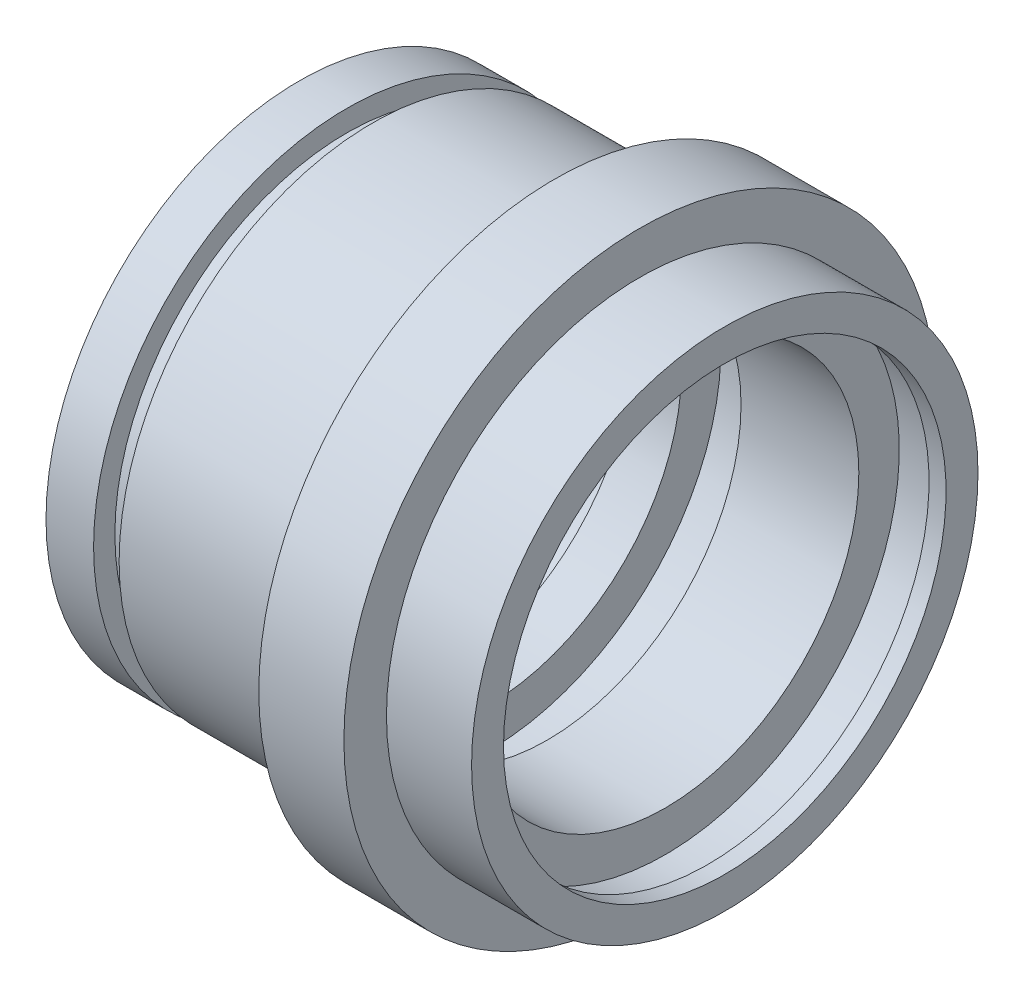
SolidWorks part; units mm, degrees
ref_plane "Front Plane" through (0, 0, 0) normal (0, 0, 1) x (1, 0, 0)
ref_plane "Top Plane" through (0, 0, 0) normal (0, 1, 0) x (1, 0, 0)
ref_plane "Right Plane" through (0, 0, 0) normal (1, 0, 0) x (0, 0, -1)
sketch "Sketch1" plane through (0, 0, 0) normal (0, 0, 1) x (1, 0, 0)
  line L0 (-25, 0) -> (25, 0) construction
  line L1 (-25, 22.75) -> (-15.49, 22.75)
  line L13 (-15.49, 22.75) -> (-15.49, 24)
  line L14 (-15.49, 24) -> (-8.49, 24)
  line L15 (-8.49, 24) -> (-8.49, 22.75)
  line L16 (-2.84, 22.75) -> (-2.84, 27.39)
  line L17 (-2.84, 27.39) -> (4.16, 27.39)
  line L18 (4.16, 27.39) -> (4.16, 22.75)
  line L19 (18, 22.75) -> (18, 27.5)
  line L20 (18, 27.5) -> (23, 27.5)
  line L21 (23, 27.5) -> (23, 26)
  line L22 (23, 26) -> (25, 26)
  line L23 (-8.49, 22.75) -> (-2.84, 22.75)
  line L24 (4.16, 22.75) -> (18, 22.75)
  line L25 (-25, 29.75) -> (25, 29.75) construction
  line L26 (-25, 34.75) -> (25, 34.75) construction
  line L29 (-25, 22.75) -> (-25, 29.75)
  line L30 (-25, 29.75) -> (-19.41, 29.75)
  line L31 (-19.41, 29.75) -> (-19.41, 27.25)
  line L32 (-19.41, 27.25) -> (-16.41, 27.25)
  line L33 (-16.41, 27.25) -> (-16.41, 29.75)
  line L34 (-16.41, 29.75) -> (5, 29.75)
  line L35 (5, 29.75) -> (5, 34.75)
  line L36 (5, 34.75) -> (15, 34.75)
  line L37 (15, 34.75) -> (15, 29.75)
  line L38 (15, 29.75) -> (25, 29.75)
  line L39 (25, 29.75) -> (25, 26)
  point P4 (0, 0)
  dimension "D1" = 50
  dimension "D2" = 22.75
  dimension "D3" = 29.75
  dimension "D4" = 7
  dimension "D5" = 5.65
  dimension "D6" = 7
  dimension "D7" = 13.84
  dimension "D8" = 34.75
  dimension "D9" = 5
  dimension "D10" = 2
  dimension "D11" = 5.59
  dimension "D12" = 3
  dimension "D13" = 21.41
  dimension "D14" = 27.25
  dimension "D15" = 10
  dimension "D16" = 24
  dimension "D17" = 27.39
  dimension "D18" = 27.5
  dimension "D19" = 22.75
  dimension "D20" = 26
revolve "Revolve1" add sketch "Sketch1" angle 360 about L0
